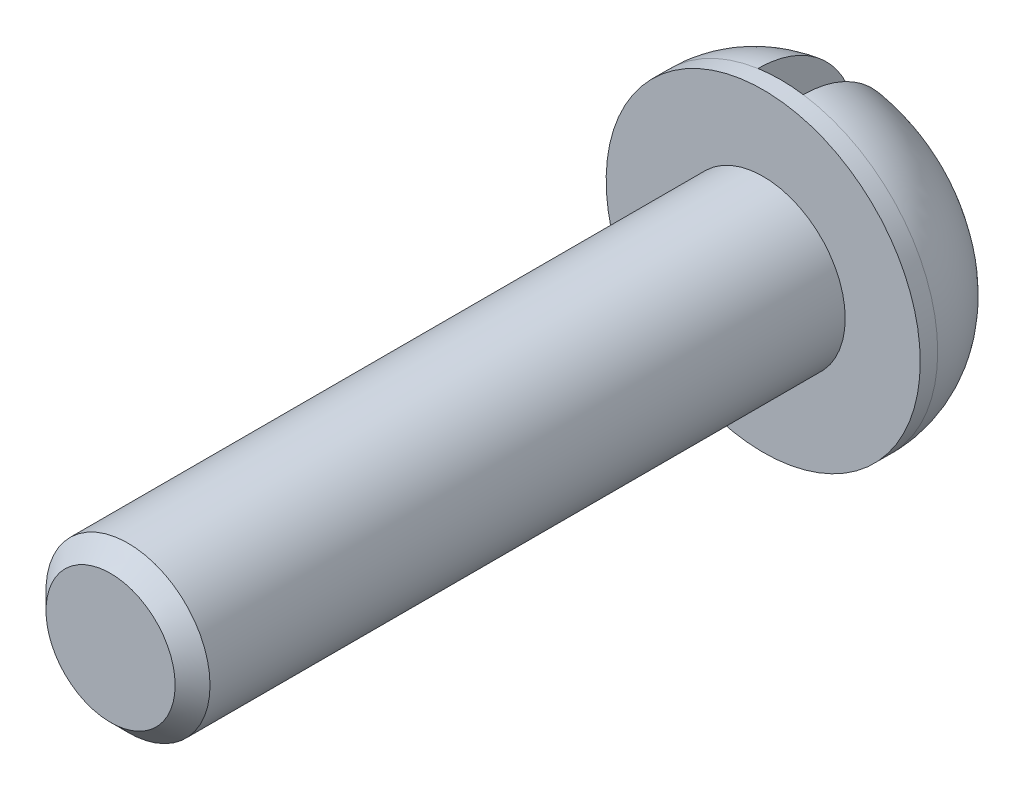
SolidWorks part; units mm, degrees
ref_plane "Plano frontal" through (0, 0, 0) normal (0, 0, 1) x (1, 0, 0)
ref_plane "Plano superior" through (0, 0, 0) normal (0, 1, 0) x (1, 0, 0)
ref_plane "Plano direito" through (0, 0, 0) normal (1, 0, 0) x (0, 0, -1)
sketch "Esboço1" plane through (0, 0, 0) normal (0, 0, 1) x (1, 0, 0)
  circle A0 centre (0, 0) radius 4.5
  dimension "D1" = 9
extrude "Ressalto-extrusão1" add sketch "Esboço1" along normal blind 3.3
sketch "Esboço2" plane through (0, 0, 0) normal (0, 0, 1) x (1, 0, 0)
  circle A0 centre (0, 0) radius 2.35
  dimension "D1" = 4.7
extrude "Ressalto-extrusão2" add sketch "Esboço2" along normal blind 22
fillet "Filete1" radius 2.8 1 edges at (4.5, 0, 0)
sketch "Esboço3" plane through (0, 0, 0) normal (0, 0, -1) x (-1, 0, 0)
  line L1 (-0.65, 5.0171) -> (0.65, 5.0171)
  line L2 (-0.65, 5.0171) -> (-0.65, -5.0171)
  line L3 (-0.65, -5.0171) -> (0.65, -5.0171)
  line L4 (0.65, 5.0171) -> (0.65, -5.0171)
  line L5 (-0.65, 5.0171) -> (0.65, -5.0171) construction
  line L6 (-0.65, -5.0171) -> (0.65, 5.0171) construction
  point P0 (0, 0)
  dimension "D1" = 1.3
extrude "Corte-extrusão1" cut sketch "Esboço3" along a picked direction on the side against the normal blind 2.8
chamfer "Chanfro1" distance 0.5 angle 45 1 edges at (2.35, 0, 22)
